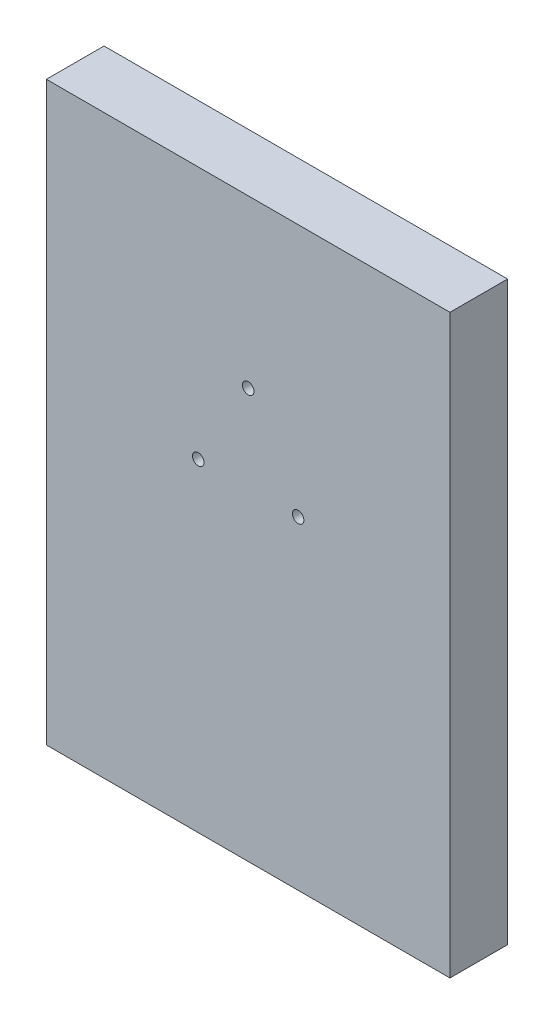
SolidWorks part; units mm, degrees
ref_plane "Front Plane" through (0, 0, 0) normal (0, 0, 1) x (1, 0, 0)
ref_plane "Top Plane" through (0, 0, 0) normal (0, 1, 0) x (1, 0, 0)
ref_plane "Right Plane" through (0, 0, 0) normal (1, 0, 0) x (0, 0, -1)
sketch "Sketch1" plane through (0, 0, 0) normal (0, 0, 1) x (1, 0, 0)
  line L1 (-35, -50) -> (35, -50)
  line L2 (-35, -50) -> (-35, 50)
  line L3 (-35, 50) -> (35, 50)
  line L4 (35, -50) -> (35, 50)
  line L5 (-35, -50) -> (35, 50) construction
  line L6 (-35, 50) -> (35, -50) construction
  point P0 (0, 0)
  dimension "D1" = 70
  dimension "D2" = 100
extrude "Boss-Extrude1" add sketch "Sketch1" along normal mid plane 10
sketch "Sketch2" plane through (0, 0, 5) normal (0, 0, 1) x (1, 0, 0)
  circle A0 centre (0, 21.0983) radius 1
  circle A3 centre (8.6603, 6.0983) radius 1
  circle A4 centre (-8.6603, 6.0983) radius 1
  point P12 (0, 11.0983)
  dimension "D2" = 2
  dimension "D1" = 3
extrude "Cut-Extrude1" cut sketch "Sketch2" against normal through all
